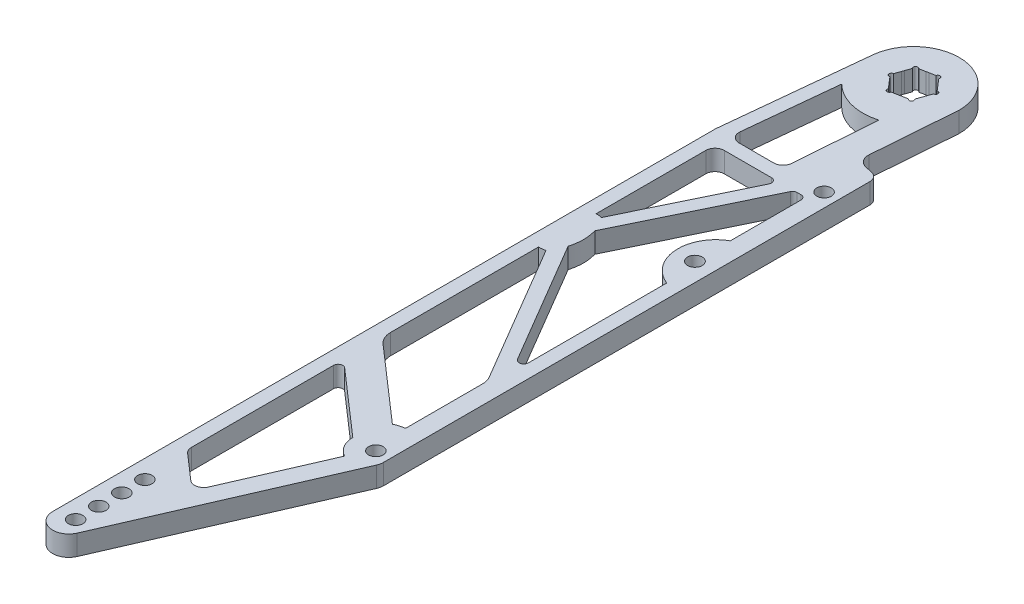
SolidWorks part; units mm, degrees
material "6061-T6 (SS)"
ref_plane "X-Y Datum" through (0, 0, 0) normal (0, 0, 1) x (1, 0, 0)
ref_plane "X-Z Datum" through (0, 0, 0) normal (0, 1, 0) x (1, 0, 0)
ref_plane "Y-Z Datum" through (0, 0, 0) normal (1, 0, 0) x (0, 0, -1)
other "Graphic1" [suppressed]
other "Graphic (Closed) -1" [suppressed]
sketch "Sketch2" plane through (0, 0, 0) normal (0, 1, 0) x (1, 0, 0)
  line L5 (13.4859, -161.3958) -> (-11.43, -139.6278) construction
  line L8 (0, 0) -> (0.7349, -24.1188) construction
  line L11 (15.3044, -26.8434) -> (13.2844, -26.3967)
  line L15 (-16.51, -220.3139) -> (-16.51, -38.0351)
  line L22 (-7.9887, -222.0863) -> (16.9799, -164.6625)
  line L23 (17.2959, -163.1433) -> (17.2959, -29.3235)
  line L33 (10.4385, -166.9668) -> (-0.894, -193.0299)
  line L44 (-8.8047, -78.8772) -> (8.7509, -42.6265)
  line L45 (9.8939, -41.91) -> (10.9459, -41.91)
  line L47 (11.153, -120.1131) -> (-8.8047, -86.2228)
  line L49 (-12.4132, -35.3011) -> (-9.8148, -9.9414)
  line L51 (3.8964, -13.4156) -> (2.1949, -35.7529)
  line L53 (-0.3377, -38.1) -> (-9.8864, -38.1)
  line L56 (2.8385, -41.91) -> (-10.16, -41.91)
  line L57 (13.97, -23.2966) -> (0, 0) construction
  line L58 (10.8042, -23.0554) -> (12.5603, 0)
  line L59 (-12.7, -146.862) -> (-12.7, -185.9568)
  line L63 (7.1359, -161.3958) -> (-10.5944, -145.9056)
  line L64 (-12.7, -74.6125) -> (-12.7, -44.45)
  line L65 (3.9815, -43.7335) -> (-11.056, -74.7846)
  line L66 (-16.4968, -37.7762) -> (-12.4949, 1.2803)
  line L67 (-4.8945, -193.9299) -> (-11.8311, -187.8696)
  line L68 (6.9813, -41.91) -> (-12.7, -82.55) construction
  line L69 (-1.1448, -63.0603) -> (-4.5739, -61.3997) construction
  line L70 (9.4184, -152.783) -> (-10.9623, -134.9772)
  line L71 (12.2159, -151.9558) -> (12.2159, -130.811)
  line L72 (11.5133, -128.2332) -> (-10.8443, -90.2675)
  line L75 (-12.7, -131.1516) -> (-12.7, -90.4875)
  line L76 (4.6927, 0.8838) -> (3.1117, -3.6221)
  line L77 (3.9022, -1.3692) -> (0, 0) construction
  line L78 (12.2159, -43.18) -> (12.2159, -62.6181)
  line L79 (13.5167, -81.4131) -> (13.5167, -119.4314)
  line L80 (0, 0) -> (-4.7752, 0) construction
  circle A0 centre (0, 0) radius 4.7752
  circle A2 centre (-11.43, -219.075) radius 2
  circle A3 centre (-11.43, -212.725) radius 2
  circle A4 centre (-11.43, -206.375) radius 2
  circle A5 centre (-11.43, -200.025) radius 2
  circle A7 centre (0, 0) radius 12.5603 construction
  circle A12 centre (13.4859, -38.1) radius 2
  arc A13 (-12.4949, 1.2803) -> (12.5603, 0) centre (0, 0) cw
  arc A14 (-8.8047, -86.2228) -> (-8.8047, -78.8772) centre (-20.962, -82.55) ccw
  circle A16 centre (24.0125, -12.7) radius 3.175 construction
  arc A17 (24.0125, -12.7) -> (13.97, -23.2966) centre (0, 0) cw construction
  circle A18 centre (13.97, -23.2966) radius 3.175 construction
  arc A19 (13.2844, -26.3967) -> (10.8042, -23.0554) centre (13.97, -23.2966) cw
  arc A20 (15.3044, -26.8434) -> (17.2959, -29.3235) centre (14.7559, -29.3235) cw
  circle A21 centre (13.4859, -161.3958) radius 2
  arc A24 (10.4385, -166.9668) -> (7.1359, -161.3958) centre (13.4859, -161.3958) cw
  arc A25 (-16.51, -220.3139) -> (-7.9887, -222.0863) centre (-12.065, -220.3139) ccw
  arc A26 (-12.7, -74.6125) -> (-11.056, -74.7846) centre (-12.7, -82.55) cw
  arc A28 (3.8964, -13.4156) -> (-9.8148, -9.9414) centre (0, 0) cw
  arc A31 (-10.16, -41.91) -> (-12.7, -44.45) centre (-10.16, -44.45) ccw
  arc A32 (-12.4132, -35.3011) -> (-9.8864, -38.1) centre (-9.8864, -35.56) ccw
  arc A33 (-0.3377, -38.1) -> (2.1949, -35.7529) centre (-0.3377, -35.56) ccw
  arc A36 (-12.7, -146.862) -> (-10.5944, -145.9056) centre (-11.43, -146.862) cw
  arc A37 (11.153, -120.1131) -> (13.5167, -119.4314) centre (12.2473, -119.4686) ccw
  arc A38 (8.7509, -42.6265) -> (9.8939, -41.91) centre (9.8939, -43.18) cw
  arc A39 (10.9459, -41.91) -> (12.2159, -43.18) centre (10.9459, -43.18) cw
  arc A40 (2.8385, -41.91) -> (3.9815, -43.7335) centre (2.8385, -43.18) cw
  arc A50 (17.2959, -163.1433) -> (16.9799, -164.6625) centre (13.4859, -163.1433) cw
  arc A52 (-16.4968, -37.7762) -> (-16.51, -38.0351) centre (-13.97, -38.0351) ccw
  arc A53 (-12.7, -185.9568) -> (-11.8311, -187.8696) centre (-10.16, -185.9568) ccw
  arc A54 (-4.8945, -193.9299) -> (-0.894, -193.0299) centre (-3.2233, -192.0171) ccw
  arc A55 (12.2159, -151.9558) -> (9.4184, -152.783) centre (13.4859, -161.3958) ccw
  arc A56 (-10.8443, -90.2675) -> (-12.7, -90.4875) centre (-12.7, -82.55) cw
  arc A57 (-12.7, -131.1516) -> (-10.9623, -134.9772) centre (-7.62, -131.1516) ccw
  arc A58 (11.5133, -128.2332) -> (12.2159, -130.811) centre (7.1359, -130.811) cw
  arc A59 (12.2159, -62.6181) -> (13.5167, -81.4131) centre (17.2959, -71.7091) ccw
  circle A60 centre (12.2159, -71.7091) radius 2.032
  point P30 (17.2959, -27.2838)
  point P44 (-2.8594, -62.23)
  point P45 (-2.2789, -196.215)
  point P75 (-4.7752, 0)
  point P88 (-12.7, -41.91)
  point P91 (-12.7, -38.1)
  point P104 (12.2159, -121.6534)
  point P107 (9.0979, -41.91)
  point P110 (13.3913, -41.91)
  point P120 (17.2959, -163.9358)
  dimension "D1" = 9.5504
  dimension "D6" = 4
  dimension "D5" = 25.1206
  dimension "D19" = 4
  dimension "D50" = 12.7
  dimension "D62" = 6.35
  dimension "D20" = 6.35
  dimension "D27" = 2.54
  dimension "D44" = 4
  dimension "D36" = 6.35
  dimension "D33" = 13.97
  dimension "D18" = 4.445
  dimension "D48" = 2.54
  dimension "D49" = 1.27
  dimension "D58" = 2.54
  dimension "D29" = 7.9375
  dimension "D31" = 3.81
  dimension "D41" = 2.54
  dimension "D54" = 9.525
  dimension "D55" = 7.9375
  dimension "D57" = 5.08
  dimension "D65" = 10.414
  dimension "D25" = 4.064
  dimension "D7" = 6.35
  dimension "D8" = 6.35
  dimension "D9" = 6.35
  dimension "D12" = 24.13
  dimension "D22" = 38.1
  dimension "D26" = 3.81
  dimension "D47" = 4.2935
  dimension "D51" = 8.262
  dimension "D56" = 3.81
  dimension "D21" = 136.652
  dimension "D43" = 200.025
  dimension "D10" = 5.08
  dimension "D28" = 38.1
  dimension "D60" = 24.0125
  dimension "D61" = 12.7
  dimension "D63" = 29.204
  dimension "D13" = 4.1084
  dimension "D17" = 13.97
  dimension "D24" = 3.81
  dimension "D30" = 2.54
  dimension "D46" = 7.62
  dimension "D11" = 5.08
  dimension "D23" = 13.4859
  dimension "D15" = 82.55
  dimension "D16" = 12.7
  dimension "D34" = 3.81
  dimension "D37" = 16.51
  dimension "D40" = 23.5
  dimension "D45" = 6.35
  dimension "D32" = 3.81
  dimension "D59" = 3.81
  dimension "D35" = 3.81
  dimension "D38" = 3.81
  dimension "D39" = 8.89
  dimension "D42" = 3.81
  dimension "D52" = 3.81
  dimension "D53" = 3.81
  dimension "D14" = 5.08
  dimension "D66" = 10.8409
  dimension "D67" = 5.08
  dimension "D64" = 4.7752
  dimension "D68" = 68.92
  dimension "D69" = 5.08
extrude "Boss-Extrude1" add sketch "Sketch2" along normal blind 5.588 contours L76 A0
sketch "Sketch6" plane through (-16.51, 0, 0) normal (-1, 0, 0) x (0, 0, 1)
  line L0 (182.2139, 5.588) -> (182.2139, 0)
  line L1 (220.3139, 0) -> (38.0351, 0) construction
  line L2 (220.3139, 5.588) -> (38.0351, 5.588) construction
  line L3 (220.3139, 5.588) -> (220.3139, 0) construction
  dimension "D1" = 38.1
split line "Split Line2"
sketch "Sketch7" plane through (0, 5.588, 0) normal (0, 1, 0) x (1, 0, 0)
  line L0 (17.2959, -163.1433) -> (17.2959, -29.3235) construction
  circle A0 centre (12.2159, -72.3621) radius 2.032
  dimension "D3" = 4.064
  dimension "D1" = 5.08
  dimension "D2" = 9.144
extrude "Cut-Extrude1" cut sketch "Sketch7" against normal up to surface (5.588 mm away) up to face at (-0.2638, 0, 126.3444)
sketch "Sketch8" plane through (0, 5.588, 0) normal (0, 1, 0) x (1, 0, 0)
  line L0 (4.6927, 0.8838) -> (3.1117, -3.6221) construction
  line L1 (1.1047, 5.0543) -> (-2.8675, 4.3062)
  line L2 (-3.8248, 3.4838) -> (-5.163, -0.3302)
  line L3 (-4.9295, -1.5704) -> (-2.2955, -4.6364)
  line L4 (-1.1047, -5.0543) -> (2.8675, -4.3062)
  line L5 (3.8248, -3.4838) -> (5.163, 0.3302)
  line L6 (4.9295, 1.5704) -> (2.2955, 4.6364)
  circle A0 centre (0, 0) radius 4.7625 construction
  arc A1 (-3.8248, 3.4838) -> (-2.8675, 4.3062) centre (-3.3924, 3.9489) cw
  arc A2 (1.1047, 5.0543) -> (2.2955, 4.6364) centre (1.7236, 4.9124) cw
  arc A3 (4.9295, 1.5704) -> (5.163, 0.3302) centre (5.116, 0.9635) cw
  arc A4 (3.8248, -3.4838) -> (2.8675, -4.3062) centre (3.3924, -3.9489) cw
  arc A5 (-1.1047, -5.0543) -> (-2.2955, -4.6364) centre (-1.7236, -4.9124) cw
  arc A6 (-4.9295, -1.5704) -> (-5.163, -0.3302) centre (-5.116, -0.9635) cw
  point P2 (-4.0022, 2.9783)
  point P4 (-2.9019, 4.2997)
  dimension "D2" = 0.635
  dimension "D5" = 0.254
  dimension "D4" = 0.254
  dimension "D1" = 9.525
  dimension "D3" = 6
extrude "Cut-Extrude2" cut sketch "Sketch8" against normal through all contours L1 A1 L2 A6 L3 A5 L4 A4 L5 A3 L6 A2
equation "\"D68@Sketch2\"=55.00+13.92"
